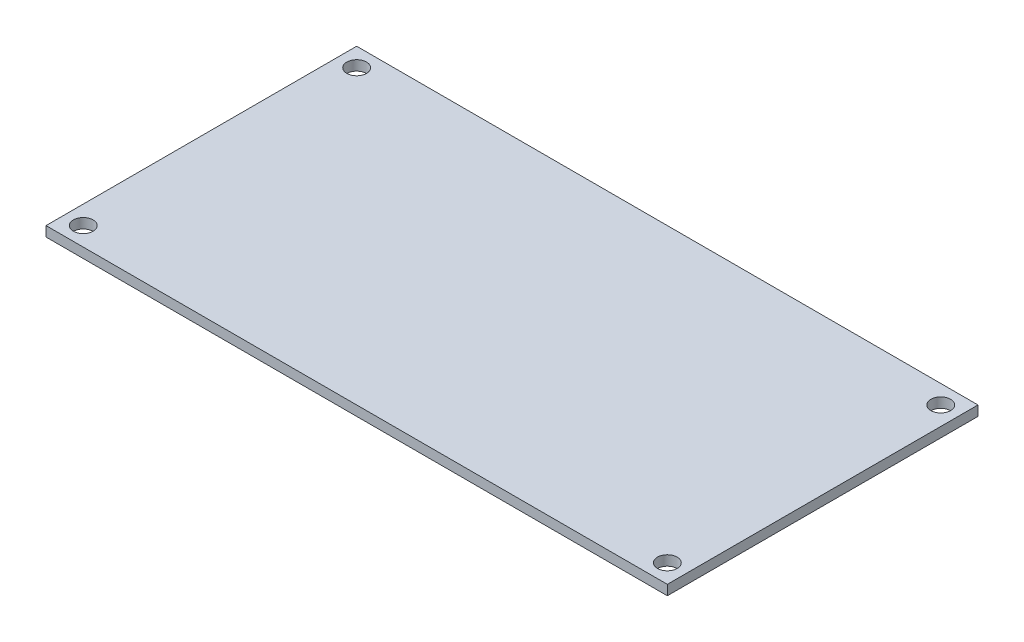
SolidWorks part; units mm, degrees
material "A-Glass Fiber"
ref_plane "Front Plane" through (0, 0, 0) normal (0, 0, 1) x (1, 0, 0)
ref_plane "Top Plane" through (0, 0, 0) normal (0, 1, 0) x (1, 0, 0)
ref_plane "Right Plane" through (0, 0, 0) normal (1, 0, 0) x (0, 0, -1)
sketch "Sketch1" plane through (0, 0, 0) normal (0, 1, 0) x (1, 0, 0)
  line L1 (0, 0) -> (100, 0)
  line L2 (0, 0) -> (0, 50)
  line L3 (0, 50) -> (100, 50)
  line L4 (100, 0) -> (100, 50)
  circle A0 centre (3, 47) radius 1.5875
  circle A1 centre (3, 3) radius 1.5875
  circle A2 centre (97, 3) radius 1.5875
  circle A3 centre (97, 47) radius 1.5875
  dimension "D3" = 3.175
  dimension "D8" = 3.175
  dimension "D11" = 3.175
  dimension "D14" = 3.175
  dimension "D1" = 100
  dimension "D2" = 50
  dimension "D4" = 3
  dimension "D5" = 3
  dimension "D6" = 3
  dimension "D7" = 3
  dimension "D9" = 3
  dimension "D10" = 3
  dimension "D12" = 3
  dimension "D13" = 3
extrude "Boss-Extrude1" add sketch "Sketch1" along normal blind 1.6
